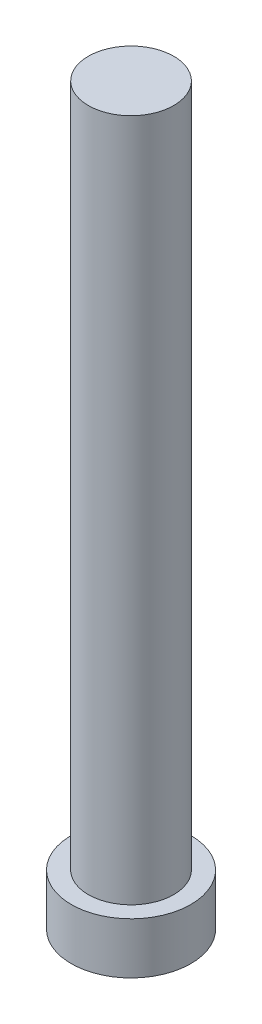
SolidWorks part; units mm, degrees
ref_plane "Front Plane" through (0, 0, 0) normal (0, 0, 1) x (1, 0, 0)
ref_plane "Top Plane" through (0, 0, 0) normal (0, 1, 0) x (1, 0, 0)
ref_plane "Right Plane" through (0, 0, 0) normal (1, 0, 0) x (0, 0, -1)
sketch "Sketch2" plane through (0, 0, 0) normal (0, 1, 0) x (1, 0, 0)
  circle A0 centre (0, 0) radius 2.5
  dimension "D1" = 5
extrude "Boss-Extrude2" add sketch "Sketch2" along normal blind 40 contours A0
sketch "Sketch3" plane through (0, 0, 0) normal (0, -1, 0) x (-1, 0, 0)
  circle A0 centre (0, 0) radius 3.5
  dimension "D1" = 7
extrude "Boss-Extrude3" add sketch "Sketch3" along normal blind 3
